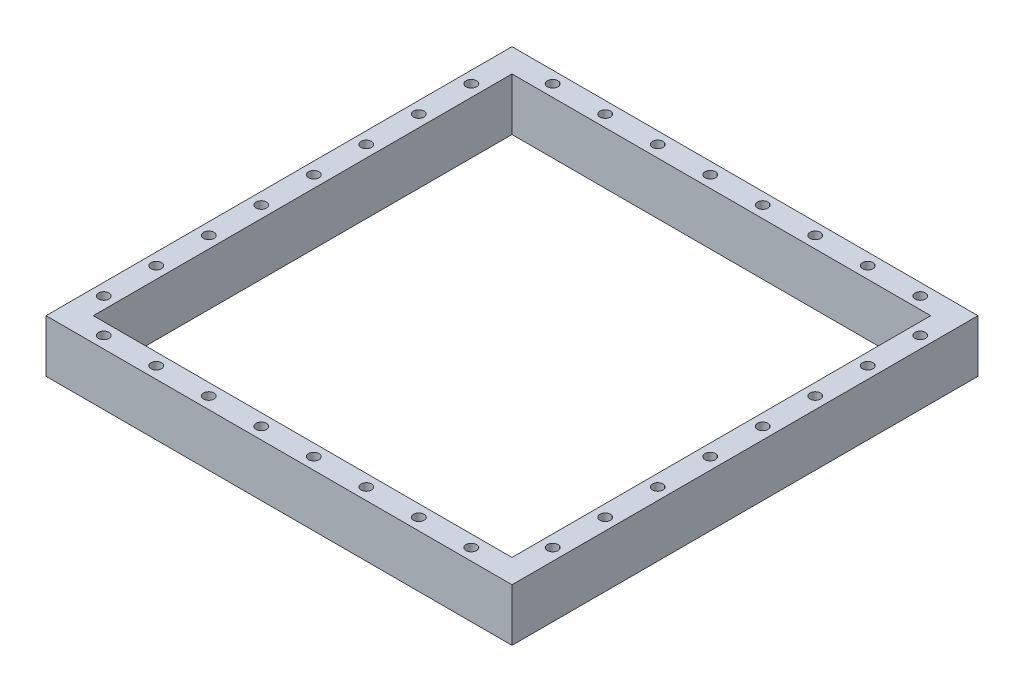
SolidWorks part; units mm, degrees
ref_plane "Front Plane" through (0, 0, 0) normal (0, 0, 1) x (1, 0, 0)
ref_plane "Top Plane" through (0, 0, 0) normal (0, 1, 0) x (1, 0, 0)
ref_plane "Right Plane" through (0, 0, 0) normal (1, 0, 0) x (0, 0, -1)
sketch "Sketch1" plane through (0, 0, 0) normal (0, 1, 0) x (1, 0, 0)
  line L1 (11.43, -11.43) -> (213.995, -11.43)
  line L2 (11.43, -11.43) -> (11.43, -213.995)
  line L3 (11.43, -213.995) -> (213.995, -213.995)
  line L4 (213.995, -11.43) -> (213.995, -213.995)
  line L7 (0, 0) -> (225.425, 0)
  line L8 (0, 0) -> (0, -225.425)
  line L9 (0, -225.425) -> (225.425, -225.425)
  line L10 (225.425, 0) -> (225.425, -225.425)
  point P0 (0, 0)
  point P6 (0, 0)
  dimension "D1" = 11.43
  dimension "D2" = 11.43
  dimension "D3" = 11.43
  dimension "D4" = 11.43
  dimension "D5" = 225.425
  dimension "D6" = 225.425
extrude "Boss-Extrude1" add sketch "Sketch1" along normal blind 25.4
hole_wizard "Tap Drill for 1/4-20 Tap1" positions "Sketch2" profile "Sketch3" hole size "1/4-20" standard "ANSI Inch"
sketch "Sketch2" plane through (0, 25.4, 0) normal (0, 1, 0) x (1, 0, 0)
  line L0 (112.7125, 0) -> (112.7125, -11.43) construction
  line L1 (225.425, 0) -> (0, 0) construction
  line L2 (213.995, -11.43) -> (11.43, -11.43) construction
  line L4 (0, -5.715) -> (225.425, -5.715) construction
  line L5 (0, 0) -> (0, -225.425) construction
  line L6 (225.425, -225.425) -> (225.425, 0) construction
  line L8 (11.43, -112.7125) -> (0, -112.7125) construction
  line L9 (11.43, -11.43) -> (11.43, -213.995) construction
  line L11 (5.715, -112.7125) -> (5.715, 0) construction
  line L13 (0, -225.425) -> (225.425, 0) construction
  point P0 (25.4, -5.715)
  point P21 (112.7125, -5.715)
  point P27 (50.8, -5.715)
  point P28 (76.2, -5.715)
  point P29 (101.6, -5.715)
  point P30 (127, -5.715)
  point P31 (152.4, -5.715)
  point P32 (177.8, -5.715)
  point P33 (203.2, -5.715)
  point P45 (5.715, -25.4)
  point P53 (5.715, -50.8)
  point P54 (5.715, -76.2)
  point P55 (5.715, -101.6)
  point P56 (5.715, -127)
  point P57 (5.715, -152.4)
  point P58 (5.715, -177.8)
  point P59 (5.715, -203.2)
  point P66 (219.71, -22.225)
  point P67 (219.71, -47.625)
  point P68 (219.71, -73.025)
  point P69 (219.71, -98.425)
  point P70 (219.71, -123.825)
  point P71 (219.71, -149.225)
  point P72 (219.71, -174.625)
  point P73 (219.71, -200.025)
  point P74 (22.225, -219.71)
  point P75 (47.625, -219.71)
  point P76 (73.025, -219.71)
  point P77 (98.425, -219.71)
  point P78 (123.825, -219.71)
  point P79 (149.225, -219.71)
  point P80 (174.625, -219.71)
  point P81 (200.025, -219.71)
  dimension "D1" = 25.4
  dimension "D3" = 25.4
  dimension "D2" = 8
  dimension "D4" = 8
sketch "Sketch3" plane through (25.4, 25.4, 5.715) normal (1, 0, 0) x (0, 0, 1)
  line L0 (0, 0) -> (0, 14.2338)
  line L1 (0, 14.2338) -> (2.5527, 12.7)
  line L2 (2.5527, 12.7) -> (2.5527, 0)
  line L5 (2.5527, 0) -> (0, 0)
  line L10 (0, 14.2338) -> (-2.5527, 12.7) construction
  line L11 (0, -6.35) -> (0, 107.95) construction
  dimension "Hole Dia." = 5.1054
  dimension "Hole Depth" = 12.7
  dimension "Drill Angle" = 118
